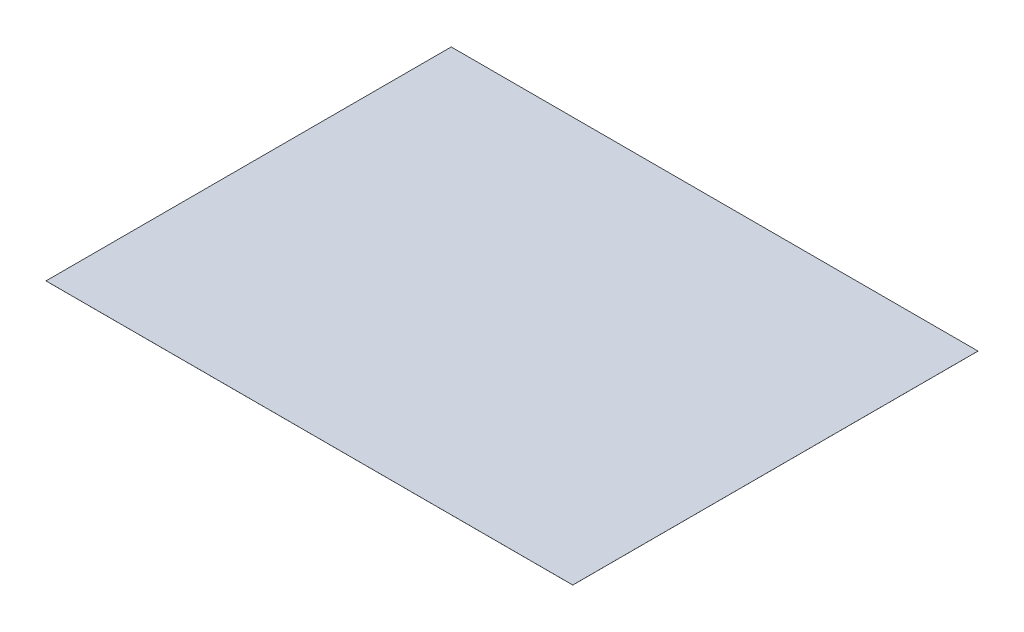
SolidWorks part; units mm, degrees
ref_plane "前视基准面" through (0, 0, 0) normal (0, 0, 1) x (1, 0, 0)
ref_plane "上视基准面" through (0, 0, 0) normal (0, 1, 0) x (1, 0, 0)
ref_plane "右视基准面" through (0, 0, 0) normal (1, 0, 0) x (0, 0, -1)
sketch "草图1" plane through (0, 0, 0) normal (0, 1, 0) x (1, 0, 0)
  line L1 (-650, -500) -> (650, -500)
  line L2 (-650, -500) -> (-650, 500)
  line L3 (-650, 500) -> (650, 500)
  line L4 (650, -500) -> (650, 500)
  line L5 (-650, -500) -> (650, 500) construction
  line L6 (-650, 500) -> (650, -500) construction
  point P0 (0, 0)
  dimension "D1" = 1300
  dimension "D2" = 1000
extrude "凸台-拉伸1" add sketch "草图1" along normal blind 0.1
